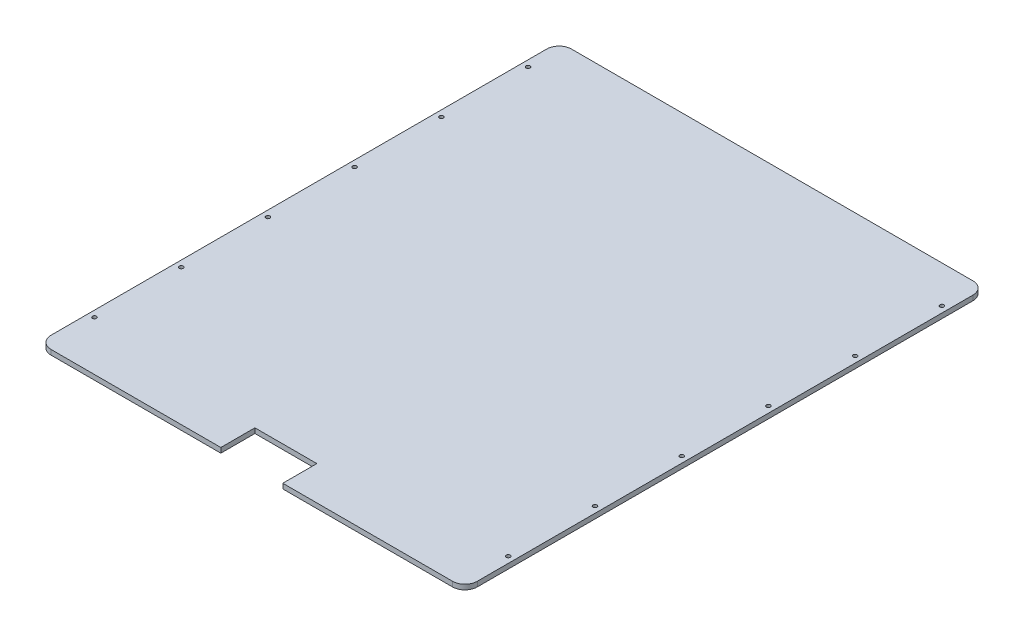
SolidWorks part; units mm, degrees
ref_plane "前视基准面" through (0, 0, 0) normal (0, 0, 1) x (1, 0, 0)
ref_plane "上视基准面" through (0, 0, 0) normal (0, 1, 0) x (1, 0, 0)
ref_plane "右视基准面" through (0, 0, 0) normal (1, 0, 0) x (0, 0, -1)
other "Configuration Table"
sketch "草图1" plane through (0, 0, 0) normal (0, 1, 0) x (1, 0, 0)
  line L1 (172, 210) -> (-172, 210)
  line L2 (172, 210) -> (172, -210)
  line L3 (172, -210) -> (-172, -210)
  line L4 (-172, 210) -> (-172, -210)
  line L5 (172, 210) -> (-172, -210) construction
  line L6 (172, -210) -> (-172, 210) construction
  line L8 (167, 194) -> (167, -170) construction
  line L10 (-167, 200) -> (-167, -170) construction
  circle A1 centre (-167, -170) radius 1.6
  circle A2 centre (167, -170) radius 1.6
  circle A3 centre (-167, -100) radius 1.6
  circle A4 centre (-167, -30) radius 1.6
  circle A5 centre (-167, 40) radius 1.6
  circle A6 centre (-167, 110) radius 1.6
  circle A7 centre (-167, 180) radius 1.6
  circle A8 centre (167, -100) radius 1.6
  circle A9 centre (167, -30) radius 1.6
  circle A10 centre (167, 40) radius 1.6
  circle A11 centre (167, 110) radius 1.6
  circle A12 centre (167, 180) radius 1.6
  point P0 (0, 0)
  point P6 (0, 0)
  dimension "D5" = 3.2
  dimension "D6" = 3.2
  dimension "D1" = 344
  dimension "D2" = 420
  dimension "D3" = 5
  dimension "D4" = 334
  dimension "D9" = 70
  dimension "D10" = 70
  dimension "D11" = 40
  dimension "D12" = 40
  dimension "D7" = 6
  dimension "D8" = 6
extrude "凸台-拉伸1" add sketch "草图1" along normal mid plane 4
sketch "草图2" plane through (0, 0, 0) normal (0, 1, 0) x (1, 0, 0)
  line L0 (0, 0) -> (0, 50000) construction
  line L1 (-172, -210) -> (172, -210) construction
  line L2 (25, -182.5) -> (-25, -182.5)
  line L3 (25, -182.5) -> (25, -210)
  line L4 (25, -210) -> (-25, -210)
  line L5 (-25, -182.5) -> (-25, -210)
  line L6 (25, -182.5) -> (-25, -210) construction
  line L7 (25, -210) -> (-25, -182.5) construction
  point P3 (0, -196.25)
  dimension "D1" = 27.5
  dimension "D2" = 50
extrude "切除-拉伸1" cut sketch "草图2" along normal through all both and the other way through all
fillet "圆角1" radius 10 4 edges at (172, 0, 210) (-172, 0, 210) (172, 0, -210) (-172, 0, -210)
